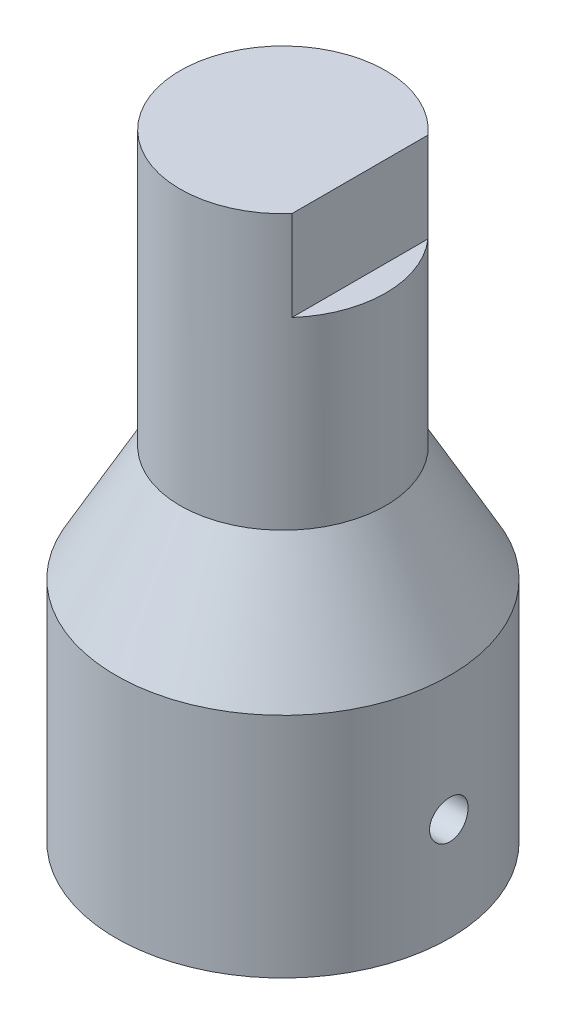
SolidWorks part; units mm, degrees
ref_plane "Front Plane" through (0, 0, 0) normal (0, 0, 1) x (1, 0, 0)
ref_plane "Top Plane" through (0, 0, 0) normal (0, 1, 0) x (1, 0, 0)
ref_plane "Right Plane" through (0, 0, 0) normal (1, 0, 0) x (0, 0, -1)
sketch "Sketch1" plane through (0, 0, 0) normal (0, 0, 1) x (1, 0, 0)
  line L0 (0, 0) -> (0, 38.1)
  line L1 (0, 38.1) -> (6.35, 38.1)
  line L2 (6.35, 38.1) -> (6.35, 21.16)
  line L3 (6.35, 21.16) -> (10.32, 14.06)
  line L4 (10.32, 14.06) -> (10.32, 0)
  line L5 (10.32, 0) -> (0, 0)
  dimension "D1" = 16.94
  dimension "D2" = 14.06
  dimension "D3" = 38.1
  dimension "D4" = 6.35
  dimension "D5" = 10.32
revolve "Revolve1" add sketch "Sketch1" angle 360 about L0
sketch "Sketch2" plane through (0, 38.1, 0) normal (0, 1, 0) x (1, 0, 0)
  line L0 (4.76, 4.203) -> (4.76, -4.203)
  line L1 (0, 0) -> (-6.35, 0) construction
  circle A0 centre (0, 0) radius 6.35 construction
  arc A1 (4.76, 4.203) -> (4.76, -4.203) centre (0, 0) ccw
  dimension "D1" = 11.11
extrude "Cut-Extrude2" cut sketch "Sketch2" against normal blind 5.56 flip side to cut
sketch "Sketch3" plane through (0, 0, 0) normal (0, -1, 0) x (1, 0, 0)
  circle A0 centre (0, 0) radius 4.765
  dimension "D1" = 9.53
extrude "Cut-Extrude3" cut sketch "Sketch3" against normal blind 14.6
sketch "Sketch4" plane through (0, 0, 0) normal (1, 0, 0) x (0, 0, -1)
  circle A0 centre (0, 6.35) radius 1.19
  dimension "D2" = 2.38
  dimension "D1" = 6.35
extrude "Cut-Extrude4" cut sketch "Sketch4" against normal through all both and the other way through all
